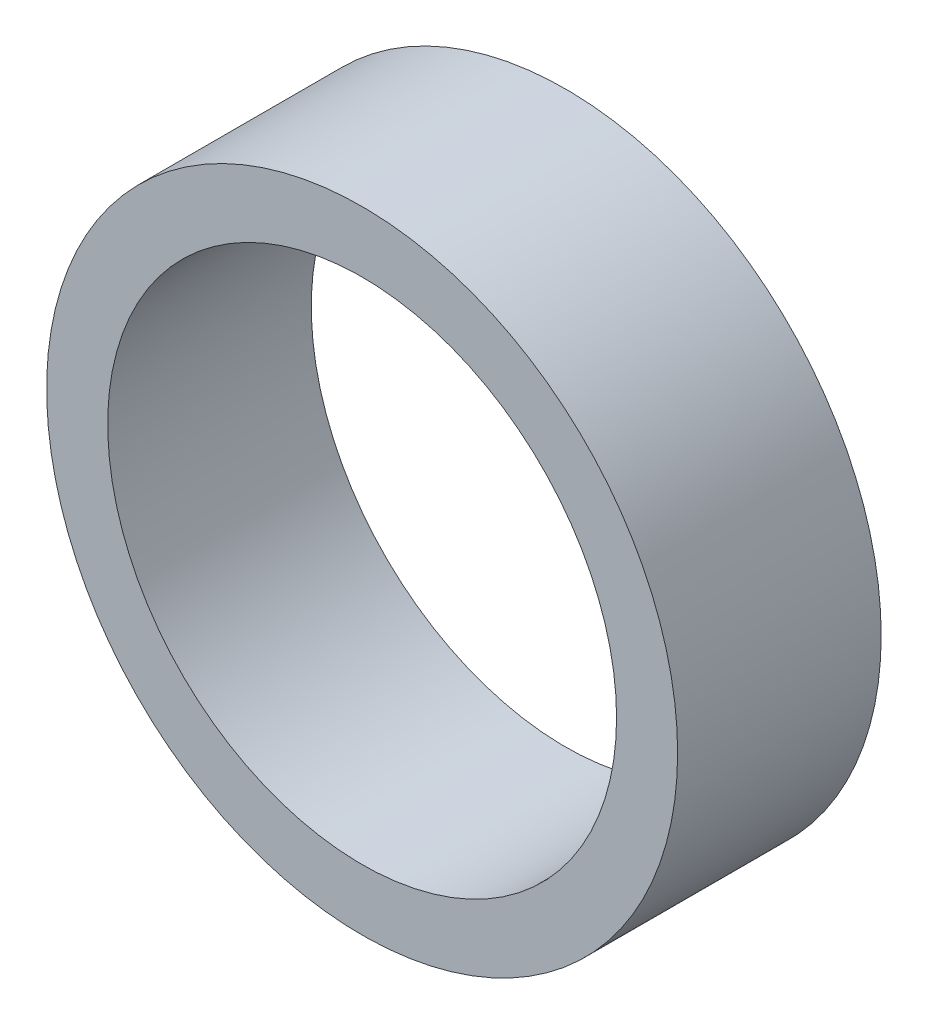
SolidWorks part; units mm, degrees
ref_plane "Płaszczyzna przednia" through (0, 0, 0) normal (0, 0, 1) x (1, 0, 0)
ref_plane "Płaszczyzna górna" through (0, 0, 0) normal (0, 1, 0) x (1, 0, 0)
ref_plane "Płaszczyzna prawa" through (0, 0, 0) normal (1, 0, 0) x (0, 0, -1)
sketch "Szkic1" plane through (0, 0, 0) normal (0, 0, 1) x (1, 0, 0)
  circle A0 centre (0, 0) radius 15.5
  circle A1 centre (0, 0) radius 12.5
  dimension "D1" = 25
  dimension "D2" = 31
extrude "Dodanie-wyciągnięcie1" add sketch "Szkic1" along normal blind 10
